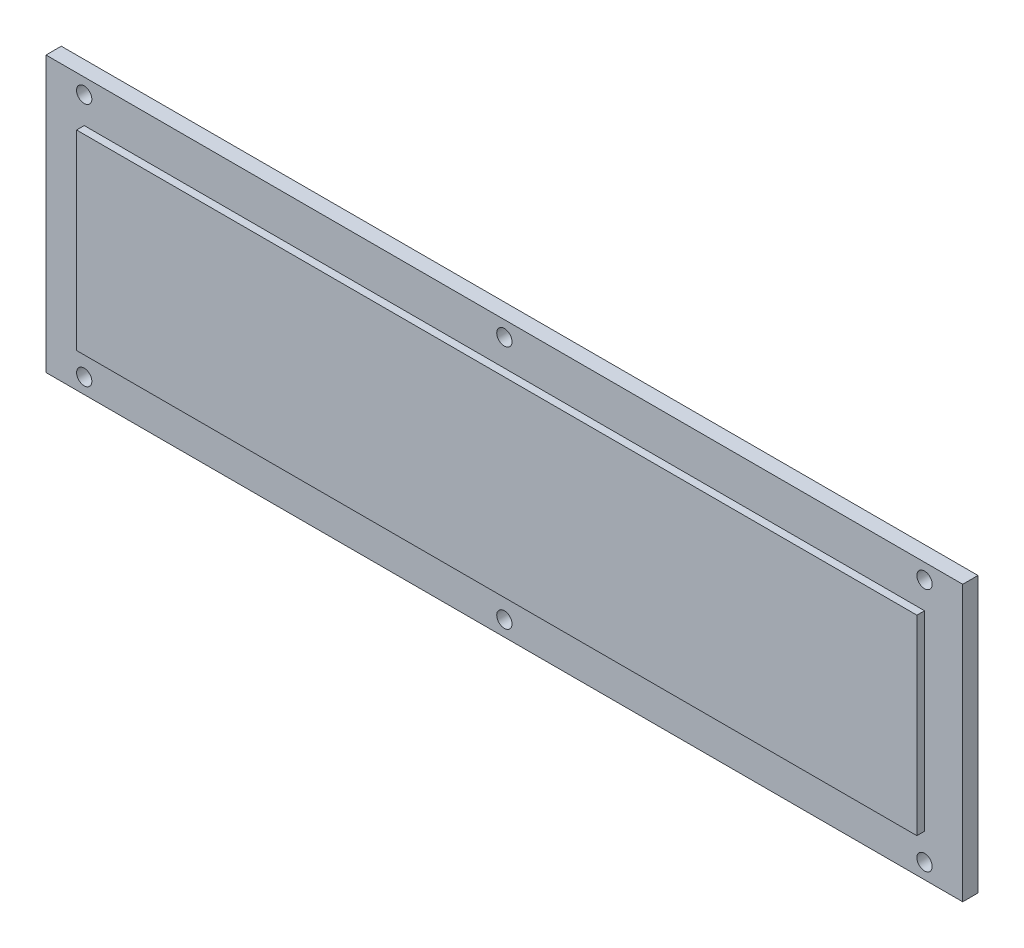
SolidWorks part; units mm, degrees
ref_plane "Front Plane" through (0, 0, 0) normal (0, 0, 1) x (1, 0, 0)
ref_plane "Top Plane" through (0, 0, 0) normal (0, 1, 0) x (1, 0, 0)
ref_plane "Right Plane" through (0, 0, 0) normal (1, 0, 0) x (0, 0, -1)
sketch "Sketch1" plane through (0, 0, 0) normal (0, 0, 1) x (1, 0, 0)
  line L1 (-60, 18) -> (60, 18)
  line L2 (-60, 18) -> (-60, -18)
  line L3 (-60, -18) -> (60, -18)
  line L4 (60, 18) -> (60, -18)
  line L5 (-60, 18) -> (60, -18) construction
  line L6 (-60, -18) -> (60, 18) construction
  point P0 (0, 0)
  dimension "D1" = 36
  dimension "D2" = 120
extrude "Boss-Extrude1" add sketch "Sketch1" along normal blind 2
sketch "Sketch2" plane through (0, 0, 2) normal (0, 0, 1) x (1, 0, 0)
  line L1 (-55, 12.5) -> (55, 12.5)
  line L2 (-55, 12.5) -> (-55, -12.5)
  line L3 (-55, -12.5) -> (55, -12.5)
  line L4 (55, 12.5) -> (55, -12.5)
  line L5 (-55, 12.5) -> (55, -12.5) construction
  line L6 (-55, -12.5) -> (55, 12.5) construction
  point P0 (0, 0)
  dimension "D1" = 110
  dimension "D2" = 25
extrude "Boss-Extrude2" add sketch "Sketch2" along normal blind 1
sketch "Sketch3" plane through (0, 0, 2) normal (0, 0, 1) x (1, 0, 0)
  line L0 (60, -18) -> (60, 18) construction
  line L1 (60, 18) -> (-60, 18) construction
  line L2 (-60, -18) -> (60, -18) construction
  line L3 (-60, 18) -> (-60, -18) construction
  circle A0 centre (-55, 16) radius 1
  circle A1 centre (-55, -16) radius 1
  circle A2 centre (55, 16) radius 1
  circle A3 centre (55, -16) radius 1
  dimension "D1" = 2
  dimension "D2" = 2
  dimension "D3" = 2
  dimension "D4" = 2
  dimension "D5" = 5
  dimension "D6" = 5
  dimension "D7" = 2
  dimension "D8" = 2
  dimension "D9" = 5
  dimension "D10" = 2
  dimension "D11" = 5
  dimension "D12" = 2
extrude "Cut-Extrude1" cut sketch "Sketch3" against normal through all
sketch "Sketch4" plane through (0, 0, 0) normal (0, 0, -1) x (-1, 0, 0)
  line L0 (60, -18) -> (-60, -18) construction
  line L1 (60, 18) -> (60, -18) construction
  circle A0 centre (0, 16) radius 1
  circle A1 centre (0, -16) radius 1
  dimension "D2" = 2
  dimension "D3" = 2
  dimension "D4" = 2
  dimension "D5" = 60
  dimension "D6" = 60
  dimension "D1" = 32
extrude "Cut-Extrude2" cut sketch "Sketch4" against normal blind 10
